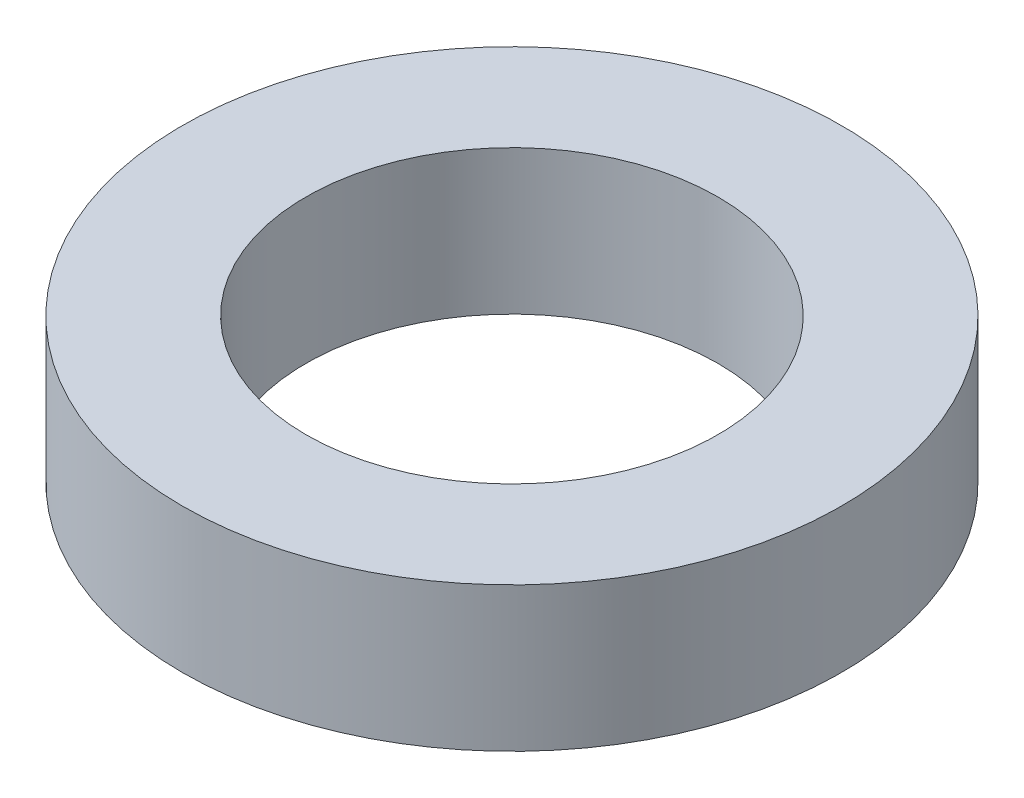
SolidWorks part; units mm, degrees
ref_plane "Front Plane" through (0, 0, 0) normal (0, 0, 1) x (1, 0, 0)
ref_plane "Top Plane" through (0, 0, 0) normal (0, 1, 0) x (1, 0, 0)
ref_plane "Right Plane" through (0, 0, 0) normal (1, 0, 0) x (0, 0, -1)
sketch "Sketch1" plane through (0, 0, 0) normal (0, 1, 0) x (1, 0, 0)
  circle A0 centre (0, 0) radius 16
  circle A1 centre (0, 0) radius 10
  dimension "D1" = 20
  dimension "D2" = 32
extrude "Boss-Extrude1" add sketch "Sketch1" along normal mid plane 7
equation "\"Ns\" = 66"
equation "\"Np_b\" = 39"
equation "\"Np_s\" = 33"
equation "\"Nr_b\" = 144"
equation "\"num_planet\" = 6"
equation "\"module\" = 0.5"
equation "\"fw_p_b\" = 18.602610884769575"
equation "\"fw_r_b\" = 18.602610884769575"
equation "\"fw_s_calc\" = 1.5726146484026726"
equation "\"fw_r_s\" = 21.05792585723615"
equation "\"fw_p_s\" = 22.55792585723615"
equation "\"fw_s_used\" = 48.660536742005725"
equation "\"pressure_angle\" = 20.0"
equation "\"motor_OD\" = 72"
equation "\"motor_height\" = 27"
equation "\"motor_mount_hole_PCD\" = 32"
equation "\"motor_mount_hole_dia\" = 4"
equation "\"motor_mount_hole_num\" = 4"
equation "\"wire_slot_dist_from_center\" = 26"
equation "\"wire_slot_length\" = 10"
equation "\"wire_slot_radius\" = 2.5"
equation "\"motor_output_hole_PCD\" = 22"
equation "\"motor_output_hole_dia\" = 3"
equation "\"motor_output_hole_num\" = 4"
equation "\"h_a\" = 0.5"
equation "\"h_f\" = 0.625"
equation "\"clr_tip_root\" = 0.125"
equation "\"dp_r_b\" = 72.0"
equation "\"db_r_b\" = 67.65786869658541"
equation "\"alpha_r_b\" = 0.8539582918412343"
equation "\"beta_r_b\" = 2.9579165836824686"
equation "\"bearing_ID\" = 60"
equation "\"bearing_OD\" = 78"
equation "\"bearing_height\" = 10"
equation "\"clearance_planet\" = 1.5"
equation "\"case_dist\" = 6.5"
equation "\"Motor_case_OD_max\" = 96.5"
equation "\"case_mounting_PCD\" = 89.0"
equation "\"bearing mount thickness\" = 8"
equation "\"case_mounting_hole_dia\" = 3"
equation "\"output_mounting_PCD\" = 86"
equation "\"output_mounting_hole_dia\" = 4"
equation "\"clearance_case_mount_holes_shell_thickness\" = 1"
equation "\"motor_case_OD_base\" = 87.0"
equation "\"sec_carrier_thickness\" = 5"
equation "\"sun_coupler_hub_thickness\" = 4"
equation "\"clearance_sun_coupler_sec_carrier\" = 1.5"
equation "\"clearance_motor_and_case\" = 5.0"
equation "\"Motor_case_thickness\" = 2.5"
equation "\"Motor_case_ID\" = 82.0"
equation "\"case_mounting_hole_shift\" = 1.0"
equation "\"output_mounting_nut_wrench_size\" = 7"
equation "\"output_mounting_nut_thickness\" = 3.2"
equation "\"case_mounting_hole_allen_socket_dia\" = 5.5"
equation "\"output_mounting_nut_depth\" = 3"
equation "\"case_mounting_bolt_depth\" = 4.5"
equation "\"ring_radial_thickness\" = 5"
equation "\"ring_OD_b\" = 82.0"
equation "\"ring_to_chamfer_clearance\" = 1.5"
equation "\"Motor_case_OD_base_to_chamfer\" = 5"
equation "\"pattern_offset_from_motor_case_OD_base\" = 3"
equation "\"pattern_bulge_dia\" = 3"
equation "\"pattern_num_bulge\" = 18"
equation "\"pattern_depth\" = 2"
equation "\"case_mounting_wrench_size\" = 5.5"
equation "\"case_mounting_nut_clearance\" = 2"
equation "\"base_plate_thickness\" = 4"
equation "\"case_mounting_nut_thickness\" = 2.4"
equation "\"case_mounting_surface_height\" = 4"
equation "\"central_hole_offset_from_motor_mount_PCD\" = 5"
equation "\"driver_upper_holes_dist_from_center\" = 29"
equation "\"driver_lower_holes_dist_from_center\" = 13"
equation "\"driver_side_holes_dist_from_center\" = 22.5"
equation "\"driver_mount_holes_dia\" = 3"
equation "\"driver_mount_inserts_OD\" = 4.8"
equation "\"driver_mount_thickness\" = 1.5"
equation "\"driver_mount_height\" = 6"
equation "\"air_flow_hole_offset\" = 3"
equation "\"pressure angle\" = 20.0"
equation "\"h_b\" = 0.625"
equation "\"planet_pin_bolt_dia\" = 5"
equation "\"planet_pin_socket_head_dia\" = 8.5"
equation "\"carrier_PCD\" = 52.5"
equation "\"planet_shaft_dia\" = 8"
equation "\"planet_shaft_step_offset\" = 1"
equation "\"carrier_trapezoidal_support_sun_offset\" = 5"
equation "\"carrier_trapezoidal_support_hole_PCD_offset_bearing_ID\" = 4"
equation "\"carrier_trapezoidal_support_hole_dia\" = 3"
equation "\"carrier_trapezoidal_support_hole_socket_head_dia\" = 5.5"
equation "\"carrier_bearing_step_width\" = 1.5"
equation "\"standard_clearance_1_5mm\" = 1.5"
equation "\"standard_fillet_1_5mm\" = 1.5"
equation "\"sun_shaft_bearing_ID\" = 8"
equation "\"sun_shaft_bearing_OD\" = 16"
equation "\"sun_shaft_bearing_width\" = 5"
equation "\"standard_bearing_insertion_chamfer\" = 0.5"
equation "\"carrier_trapezoidal_support_hole_wrench_size\" = 5.5"
equation "\"planet_pin_bolt_wrench_size\" = 8"
equation "\"planet_bearing_OD\" = 12"
equation "\"planet_bearing_width\" = 3.5"
equation "\"planet_bore\" = 10"
equation "\"dp_s\" = 33.0"
equation "\"db_s\" = 31.00985648593498"
equation "\"alpha_s\" = 0.8539582918412449"
equation "\"beta_s\" = 1.0193561435902372"
equation "\"dp_p_b\" = 19.5"
equation "\"db_p_b\" = 18.324006105325214"
equation "\"alpha_p_b\" = 0.8539582918412414"
equation "\"beta_p_b\" = 2.907468031702132"
equation "\"sun_hub_dia\" = 28.0"
equation "\"sun_central_bolt_dia\" = 5"
equation "\"sun_central_bolt_socket_head_dia\" = 8.5"
equation "\"motor_output_hole_CSK_OD\" = 6"
equation "\"motor_output_hole_CSK_head_height\" = 1.5"
equation "\"bearing_retainer_thickness\" = 2"
equation "\"dp_p_s\" = 16.5"
equation "\"db_p_s\" = 15.50492824296749"
equation "\"alpha_p_s\" = 0.8539582918412449"
equation "\"beta_p_s\" = 3.7466288708629643"
equation "\"Nr_s\" = 138"
equation "\"clr_tip_root_s\" = 0.125"
equation "\"dp_r_s\" = 69.0"
equation "\"db_r_s\" = 64.83879083422768"
equation "\"alpha_r_s\" = 0.8539582918412485"
equation "\"beta_r_s\" = 3.0122644097694535"
equation "\"small_ring_case_thickness\" = 4"
equation "\"carrier_thickness\" = 4"
equation "\"small_ring_output_wall_thickness\" = 5"
equation "\"small_ring_output_wall_to_bearing_shaft_attachement_hole_dia\" = 4"
equation "\"small_ring_output_wall_to_bearing_shaft_attachement_hole_depth\" = 6.5"
equation "\"small_ring_output_wall_to_bearing_shaft_attachement_nut_wrench\" = 7"
equation "\"small_ring_output_wall_to_bearing_shaft_attachement_nut_thickness\" = 3.2"
equation "\"small_ring_output_wall_to_bearing_shaft_attachement_hole_pcd\" = 12"
equation "\"small_ring_output_wall_to_bearing_shaft_attachement_hole_num\" = 3"
equation "\"small_ring_output_wall_to_bearing_shaft_attachement_hole_CSK_OD\" = 8"
equation "\"small_ring_output_wall_to_bearing_shaft_attachement_hole_CSK_head_height\" = 2.0"
equation "\"carrier_small_ring_inner_bearing_ID\" = 20"
equation "\"carrier_small_ring_inner_bearing_OD\" = 32"
equation "\"carrier_small_ring_inner_bearing_height\" = 7"
equation "\"carrier_small_ring_inner_bearing_flap\" = 2"
equation "\"D1@Boss-Extrude1\"=\"carrier_small_ring_inner_bearing_height\""
equation "\"D1@Sketch1\"=\"carrier_small_ring_inner_bearing_ID\""
equation "\"D2@Sketch1\"=\"carrier_small_ring_inner_bearing_OD\""
